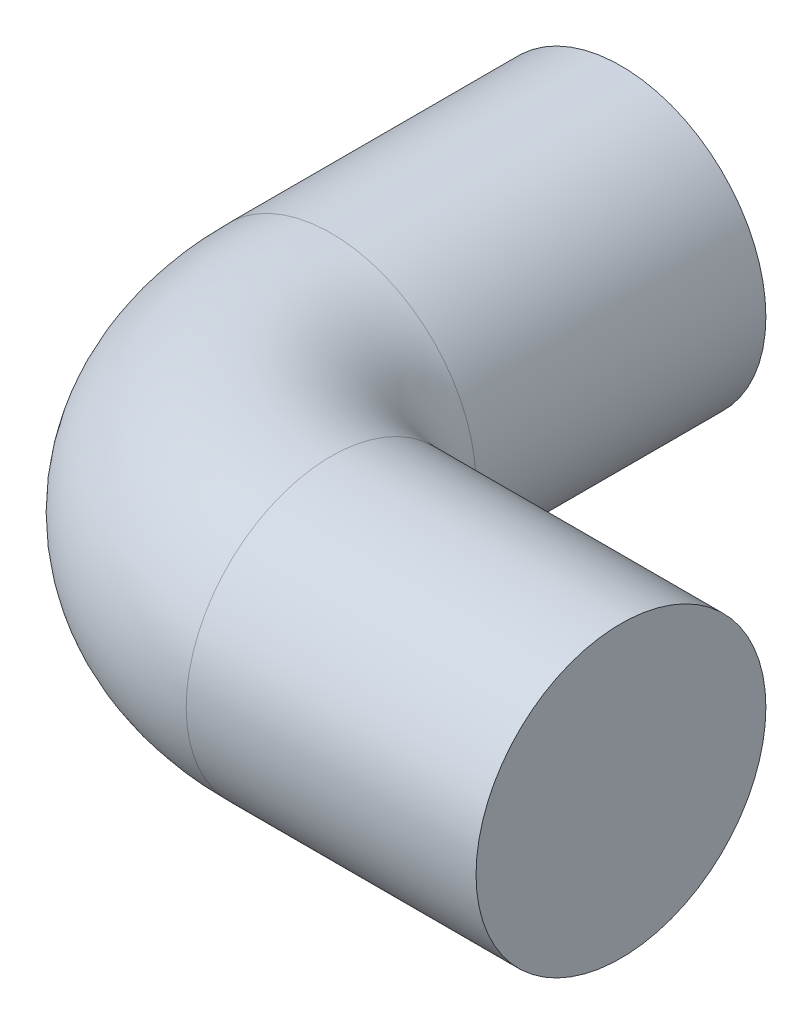
SolidWorks part; units mm, degrees
ref_plane "Front Plane" through (0, 0, 0) normal (0, 0, 1) x (1, 0, 0)
ref_plane "Top Plane" through (0, 0, 0) normal (0, 1, 0) x (1, 0, 0)
ref_plane "Right Plane" through (0, 0, 0) normal (1, 0, 0) x (0, 0, -1)
sketch "Sketch1" plane through (0, 0, 0) normal (0, 1, 0) x (1, 0, 0)
  line L0 (0, 0) -> (-75, 0)
  line L1 (-125, 50) -> (-125, 125)
  arc A0 (-75, 0) -> (-125, 50) centre (-75, 50) cw
  dimension "D1" = 75
  dimension "D2" = 75
  dimension "D3" = 50
  dimension "D4" = 50
sweep "Sweep1" add path "Sketch1" circular profile diameter 75 parameters "D3"=75
